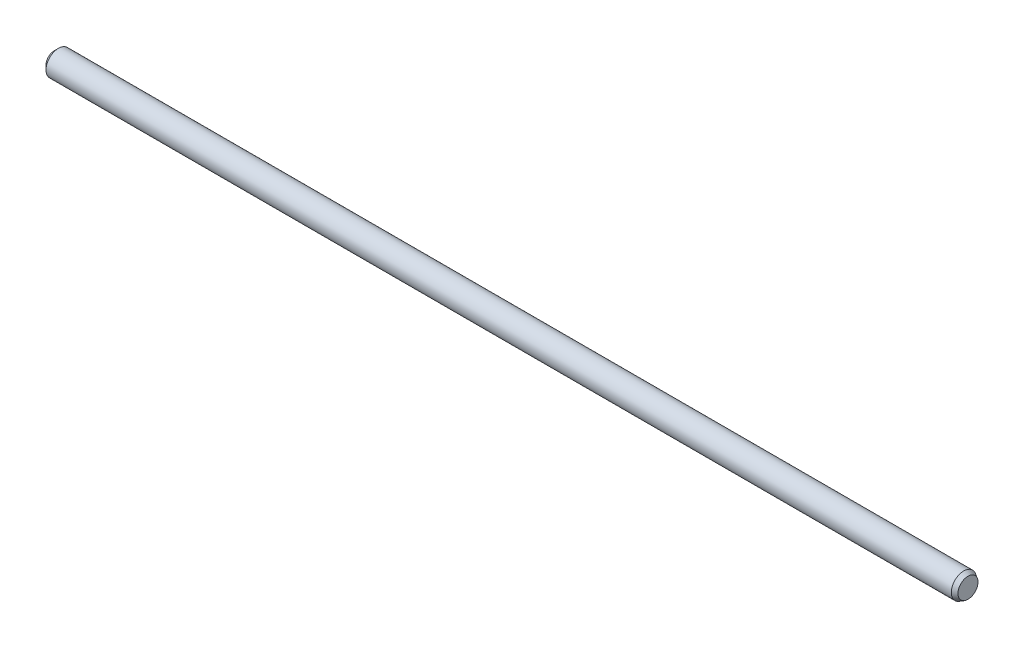
SolidWorks part; units mm, degrees
ref_plane "Alzado" through (0, 0, 0) normal (0, 0, 1) x (1, 0, 0)
ref_plane "Planta" through (0, 0, 0) normal (0, 1, 0) x (1, 0, 0)
ref_plane "Vista lateral" through (0, 0, 0) normal (1, 0, 0) x (0, 0, -1)
sketch "Croquis1" plane through (0, 0, 0) normal (1, 0, 0) x (0, 0, -1)
  circle A0 centre (0, 0) radius 1.475
  dimension "D1" = 2.95
extrude "Saliente-Extruir1" add sketch "Croquis1" along normal blind 108
chamfer "Chaflán1" distance 0.5 angle 30 1 edges at (108, 0, -1.475)
chamfer "Chaflán2" distance 0.5 angle 45 1 edges at (0, 0, -1.475)
